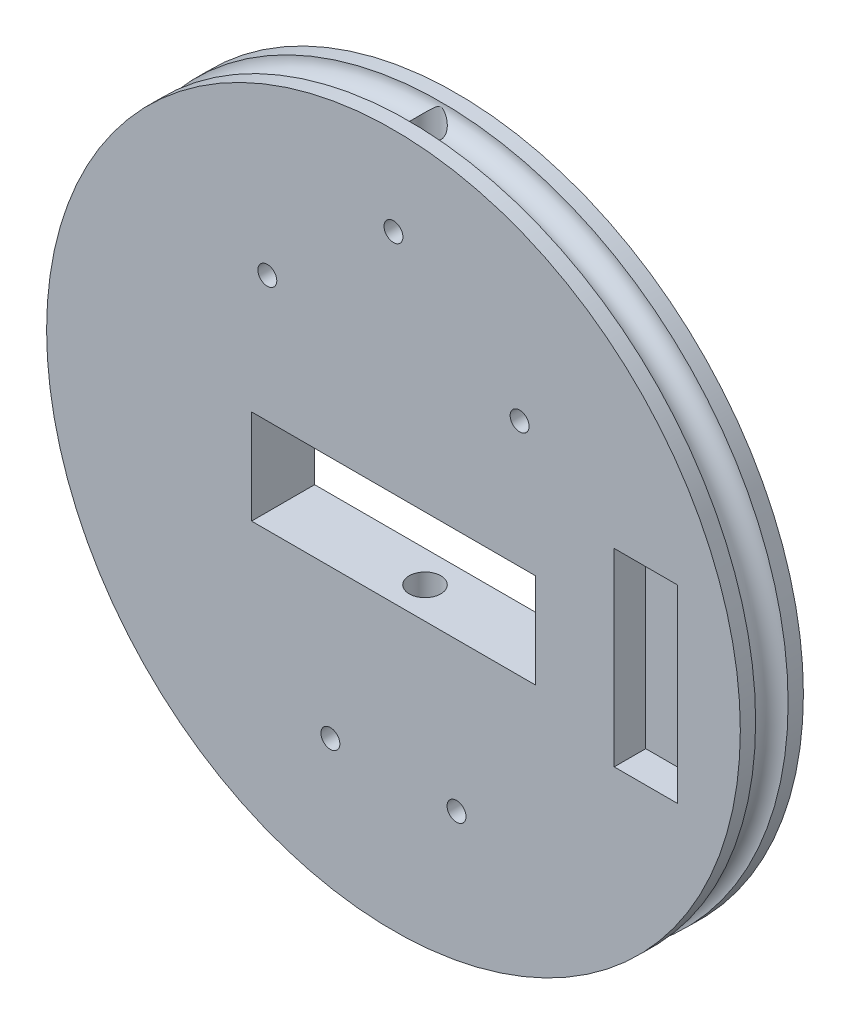
SolidWorks part; units mm, degrees
ref_plane "Alzado" through (0, 0, 0) normal (0, 0, 1) x (1, 0, 0)
ref_plane "Planta" through (0, 0, 0) normal (0, 1, 0) x (1, 0, 0)
ref_plane "Vista lateral" through (0, 0, 0) normal (1, 0, 0) x (0, 0, -1)
sketch "Croquis1" plane through (0, 0, 0) normal (0, 0, 1) x (1, 0, 0)
  line L1 (-22.5, -10) -> (22.5, -10)
  line L2 (-22.5, -10) -> (-22.5, 5)
  line L3 (-22.5, 5) -> (22.5, 5)
  line L4 (22.5, -10) -> (22.5, 5)
  circle A0 centre (0, 0) radius 55
  dimension "D1" = 110
  dimension "D2" = 10
  dimension "D3" = 5
  dimension "D4" = 45
  dimension "D5" = 22.5
extrude "Saliente-Extruir1" add sketch "Croquis1" along normal blind 10
sketch "Croquis2" plane through (0, 0, 10) normal (0, 0, 1) x (1, 0, 0)
  line L0 (-69.3522, 0) -> (69.121, 0) construction
  line L1 (0, 62.8793) -> (0, -67.9652) construction
  line L3 (25, -15) -> (35, -15)
  line L4 (25, -15) -> (25, 15)
  line L5 (25, 15) -> (35, 15)
  line L6 (35, -15) -> (35, 15)
  line L7 (25, -15) -> (35, 15) construction
  line L8 (25, 15) -> (35, -15) construction
  point P5 (30, 0)
  dimension "D1" = 30
  dimension "D2" = 35
  dimension "D3" = 10
extrude "Saliente-Extruir2" add sketch "Croquis2" along normal blind 65
sketch "Croquis3" plane through (0, -15, 0) normal (0, -1, 0) x (1, 0, 0)
  line L0 (25, 75) -> (35, 75) construction
  line L1 (25, 75) -> (25, 10) construction
  circle A0 centre (30, 70) radius 1.5
  dimension "D1" = 3
  dimension "D2" = 5
  dimension "D3" = 5
extrude "Cortar-Extruir1" cut sketch "Croquis3" against normal blind 50
sketch "Croquis4" plane through (0, -15, 0) normal (0, -1, 0) x (1, 0, 0)
  line L0 (35, 65) -> (25, 42.6024)
  line L1 (25, 65) -> (35, 65) construction
  line L2 (25, 65) -> (25, 75)
  line L3 (25, 75) -> (35, 75)
  line L4 (35, 65) -> (35, 75)
  line L5 (25, 65) -> (35, 75) construction
  line L6 (34.1967, 65.8033) -> (35, 65) construction
  line L7 (25, 75) -> (25, 10) construction
  line L8 (25, 42.6024) -> (25, 65)
  point P0 (30, 70)
extrude "Cortar-Extruir2" cut sketch "Croquis4" against normal blind 10
mirror "Simetría1" about plane through (0, 0, 0) normal (0, 1, 0) of "Cortar-Extruir2"
sketch "Croquis5" plane through (0, 5, 0) normal (0, -1, 0) x (1, 0, 0)
  line L0 (55, 10) -> (-55, 10) construction
  circle A0 centre (0, 5) radius 2.5
  dimension "D1" = 5
  dimension "D2" = 5
extrude "Cortar-Extruir3" cut sketch "Croquis5" against normal mid plane 170
sketch "Croquis6" plane through (0, 0, 10) normal (0, 0, 1) x (1, 0, 0)
  line L0 (0, 0) -> (0, 230.7937) construction
  line L1 (-2.5, 48.5) -> (2.5, 48.5) construction
  line L2 (-6, 21.6) -> (6, 21.6)
  line L3 (-6, 21.6) -> (-6, 53.6)
  line L4 (-6, 53.6) -> (6, 53.6)
  line L5 (6, 21.6) -> (6, 53.6)
  line L6 (-6, 21.6) -> (6, 53.6) construction
  line L7 (-6, 53.6) -> (6, 21.6) construction
  line L8 (0, 0) -> (0, -76.3571) construction
  line L9 (-20, -34.75) -> (20, -34.75) construction
  line L10 (-20, -10) -> (20, -10)
  line L11 (-20, -10) -> (-20, -5)
  line L12 (-20, -5) -> (20, -5)
  line L13 (20, -10) -> (20, -5)
  line L14 (-20, -10) -> (20, -5) construction
  line L15 (-20, -5) -> (20, -10) construction
  line L16 (-6, -59.5) -> (6, -59.5)
  line L17 (-6, -59.5) -> (-6, -10)
  line L18 (-6, -10) -> (6, -10)
  line L19 (6, -59.5) -> (6, -10)
  line L20 (-6, -59.5) -> (6, -10) construction
  line L21 (-6, -10) -> (6, -59.5) construction
  circle A0 centre (0, 48.5) radius 2.5
  circle A4 centre (0, 48.5) radius 2.5 construction
  point P3 (0, 37.6)
  point P15 (0, -7.5)
  point P22 (0, -34.75)
  dimension "D3" = 5
  dimension "D1" = 32
  dimension "D2" = 12
  dimension "D4" = 5.1
  dimension "D5" = 40
  dimension "D6" = 5
  dimension "D7" = 7.5
  dimension "D8" = 49.5
sketch "Croquis7" plane through (0, 0, 10) normal (0, 0, 1) x (1, 0, 0)
  line L1 (0, 0) -> (0, 55) construction
  line L2 (0, 0) -> (0, 230.7937) construction
  circle A0 centre (0, 41) radius 1.5
  circle A2 centre (0, 0) radius 55 construction
  dimension "D1" = 3
  dimension "D2" = 41
sketch "Croquis8" plane through (0, 0, 10) normal (0, 0, 1) x (1, 0, 0)
  line L0 (-20, 25) -> (16.3728, 25) construction
  line L1 (0, 0) -> (0, 230.7937) construction
  line L2 (-10, -33.6) -> (16.3728, -33.6) construction
  line L3 (-22.5, -10) -> (22.5, -10) construction
  line L4 (22.5, 5) -> (-22.5, 5) construction
  line L11 (0, 55) -> (0, 20.199) construction
  line L20 (0, 0) -> (0, -55) construction
  line L21 (0, 0) -> (0, -76.3571) construction
  circle A0 centre (10, -33.6) radius 1.5
  circle A1 centre (20, 25) radius 1.5
  circle A2 centre (0, 0) radius 55 construction
  circle A3 centre (0, 41) radius 1.5 construction
  circle A16 centre (-20, 25) radius 1.5
  circle A17 centre (-10, -33.6) radius 1.5
  dimension "D1" = 23.6
  dimension "D6" = 3
  dimension "D7" = 3
  dimension "D5" = 3
  dimension "D2" = 20
  dimension "D3" = 20
  dimension "D4" = 41
  dimension "D8" = 16
extrude "Cortar-Extruir4" cut sketch "Croquis8" against normal blind 10
sketch "Croquis10" plane through (0, 0, 0) normal (0, 1, 0) x (1, 0, 0)
  line L0 (0, 0) -> (0, -45.7171) construction
  line L2 (-55, 0) -> (-55, -10) construction
  line L3 (55, 0) -> (-55, 0) construction
  line L4 (-55, -10) -> (55, -10) construction
  circle A0 centre (-55, -5) radius 2.575
  dimension "D1" = 5.15
revolve "Cortar-Revolución1" cut sketch "Croquis10" angle 360 about L0
sketch "Croquis11" plane through (0, 15, 0) normal (0, 1, 0) x (1, 0, 0)
  line L0 (35, -10) -> (25, -10) construction
  line L1 (35, -75) -> (25, -75)
  line L2 (35, -75) -> (35, -5)
  line L3 (35, -5) -> (25, -5)
  line L4 (25, -75) -> (25, -5)
  dimension "D1" = 5
extrude "Cortar-Extruir5" cut sketch "Croquis11" against normal up to surface (30 mm away) up to face at (30, -15, 31.9006)
sketch "Croquis12" plane through (0, 15, 0) normal (0, -1, 0) x (1, 0, 0)
  line L1 (35, 10) -> (45, 10)
  line L3 (35, 5) -> (45, 5)
  line L4 (35, 10) -> (25, 10)
  line L5 (25, 10) -> (25, 5)
  line L6 (25, 5) -> (35, 5)
  line L7 (35, 5) -> (35, 10)
  line L8 (35, 10) -> (25, 10)
  line L9 (25, 10) -> (25, 5)
  line L10 (25, 5) -> (35, 5)
  line L12 (45, 10) -> (45, 5)
  dimension "D2" = 20
  dimension "D1" = 0
extrude "Cortar-Extruir6" cut sketch "Croquis12" along normal up to surface (30 mm away) up to face at (30, -15, 7.5)
sketch "Croquis13" plane through (0, 0, 10) normal (0, 0, 1) x (1, 0, 0)
  line L0 (45, 15) -> (25, 15) construction
  line L1 (25, -15) -> (35, -15)
  line L2 (25, -15) -> (25, 15)
  line L3 (25, 15) -> (35, 15)
  line L4 (35, -15) -> (35, 15)
  dimension "D1" = 10
extrude "Saliente-Extruir4" add sketch "Croquis13" against normal up to next
extrude "Cortar-Extruir9" cut sketch "Croquis7" against normal blind 10 contours A0
